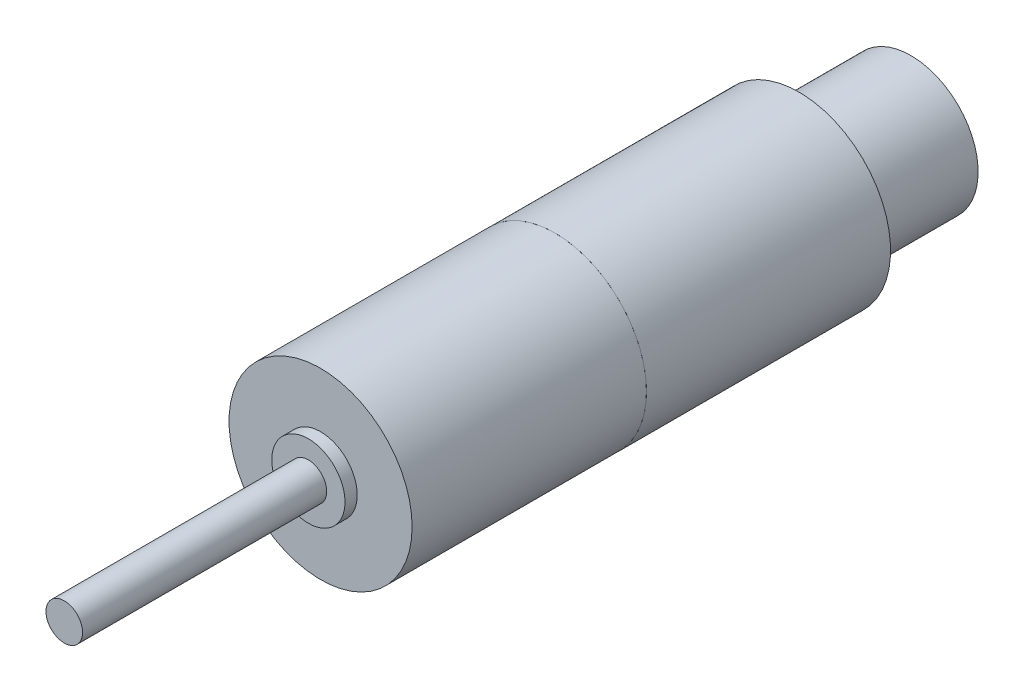
SolidWorks part; units mm, degrees
material "1060 Alloy"
ref_plane "Front Plane" through (0, 0, 0) normal (0, 0, 1) x (1, 0, 0)
ref_plane "Top Plane" through (0, 0, 0) normal (0, 1, 0) x (1, 0, 0)
ref_plane "Right Plane" through (0, 0, 0) normal (1, 0, 0) x (0, 0, -1)
sketch "Sketch1" plane through (0, 0, 0) normal (0, 0, 1) x (1, 0, 0)
  circle A0 centre (0, 0) radius 15
  dimension "D1" = 30
extrude "Boss-Extrude1" add sketch "Sketch1" along normal blind 38.4 contours A0
sketch "Sketch2" plane through (0, 0, 0) normal (0, 0, -1) x (-1, 0, 0)
  circle A0 centre (0, 0) radius 15
extrude "Boss-Extrude2" add sketch "Sketch2" along normal blind 40 separate body
sketch "Sketch3" plane through (0, 0, 38.4) normal (0, 0, 1) x (1, 0, 0)
  circle A0 centre (0, 0) radius 6
extrude "Boss-Extrude3" add sketch "Sketch3" along normal blind 2 contours A0
sketch "Sketch4" plane through (0, 0, -40) normal (0, 0, -1) x (-1, 0, 0)
  circle A0 centre (0, 0) radius 11
extrude "Boss-Extrude4" add sketch "Sketch4" along normal blind 18.35 separate body contours A0
sketch "Sketch5" plane through (0, 0, 40.4) normal (0, 0, 1) x (1, 0, 0)
  circle A0 centre (0, 0) radius 3
extrude "Boss-Extrude5" add sketch "Sketch5" along normal blind 40 separate body contours A0
